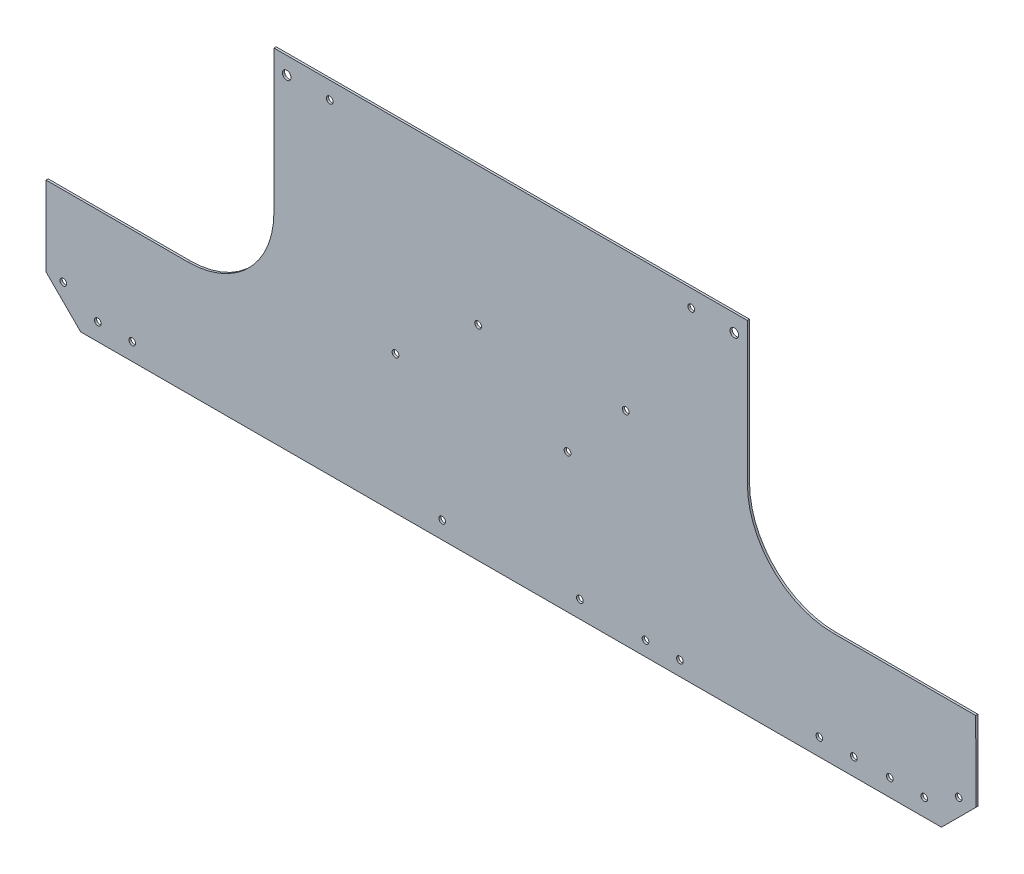
SolidWorks part; units mm, degrees
material "Perspex (TM) GS Acrylic Cast Sheet"
ref_plane "Front Plane" through (0, 0, 0) normal (0, 0, 1) x (1, 0, 0)
ref_plane "Top Plane" through (0, 0, 0) normal (0, 1, 0) x (1, 0, 0)
ref_plane "Right Plane" through (0, 0, 0) normal (1, 0, 0) x (0, 0, -1)
sketch "Sketch1" plane through (0, 0, 0) normal (0, 0, 1) x (1, 0, 0)
  line L1 (-457.2, -304.8) -> (457.2, -304.8)
  line L2 (-457.2, -304.8) -> (-457.2, 304.8)
  line L3 (-457.2, 304.8) -> (457.2, 304.8)
  line L4 (457.2, -304.8) -> (457.2, 304.8)
  line L5 (0, 304.8) -> (0, -304.8) construction
  line L6 (-457.2, 0) -> (457.2, 0) construction
  point P0 (0, 0)
  point P4 (-320.04, 0)
  point P5 (320.04, 0)
  point P6 (0, 213.36)
  point P7 (0, -213.36)
  dimension "Length" = 914.4
  dimension "Width" = 609.6
  dimension "Break" = 137.16
  dimension "D2" = 137.16
  dimension "D1" = 91.44
  dimension "D3" = 91.44
sketch "Sketch2" plane through (0, 0, 0) normal (1, 0, 0) x (0, 0, -1)
  line L0 (-0.7938, -304.8) -> (0.7938, -304.8)
  dimension "Thickness" = 1.5875
sketch "Sketch3" plane through (0, 0, 0) normal (0, 0, 1) x (1, 0, 0)
  line L0 (-457.2, -304.8) -> (-457.2, 304.8) construction
  line L1 (-457.2, -304.8) -> (457.2, -304.8) construction
  line L2 (457.2, -304.8) -> (457.2, 304.8) construction
  line L3 (-457.2, 304.8) -> (457.2, 304.8) construction
  line L4 (-457.2, -304.8) -> (-457.2, 304.8)
  line L5 (-457.2, -304.8) -> (457.2, -304.8)
  line L6 (457.2, -304.8) -> (457.2, 304.8)
  line L7 (-457.2, 304.8) -> (457.2, 304.8)
extrude "Boss-Extrude1" add sketch "Sketch3" along normal mid plane 1.5875
sketch "Sketch4" plane through (0, 0, 0.7937) normal (0, 0, 1) x (1, 0, 0)
  line L1 (-362.5066, 0.4474) -> (318.2125, 1.5649)
  line L2 (-339.2322, -251.9272) -> (-364.674, -226.4854)
  line L5 (-363.9625, -659.9558) -> (-365.0466, 0.4433) construction
  line L12 (-364.674, -226.4854) -> (-365.0424, -2.0967)
  line L15 (-339.2322, -251.9272) -> (295.7669, -250.8848)
  line L26 (295.7669, -250.8848) -> (321.1253, -225.5264)
  line L27 (320.7942, -23.8309) -> (321.8783, -684.23) construction
  line L28 (321.1253, -225.5264) -> (320.7567, -0.9709)
  arc A2 (318.2125, 1.5649) -> (320.7567, -0.9709) centre (318.2167, -0.9751) cw
  arc A3 (-362.5066, 0.4474) -> (-365.0424, -2.0967) centre (-362.5024, -2.0926) ccw
  point P12 (320.7525, 1.5691)
  point P15 (-365.0466, 0.4433)
  dimension "D1" = 2.54
  dimension "D2" = 2.54
extrude "Cut-Extrude1" cut sketch "Sketch4" against normal blind 2.54 flip side to cut
sketch "Sketch12" plane through (0, 0, -0.7937) normal (0, 0, -1) x (-1, 0, 0)
  line L1 (196.6362, -104.0919) -> (196.6362, 20.4048)
  line L19 (196.6362, 20.4048) -> (384.7638, 20.0959)
  line L20 (384.4556, -167.696) -> (384.7638, 20.0959)
  line L21 (260.0319, -167.696) -> (384.4556, -167.696)
  arc A2 (260.0319, -167.696) -> (196.6362, -104.0919) centre (260.1362, -104.1961) cw
sketch "Sketch9" plane through (0, 0, 0.7937) normal (0, 0, 1) x (1, 0, 0)
  point P0 (-365.5467, -279.4147)
  point P1 (-339.7911, -292.1147)
  point P3 (-314.3911, -292.1147)
  point P5 (-365.5467, -229.8463)
  point P15 (270.1645, -292.1147)
  point P17 (295.5645, -292.1147)
  point P19 (321.3201, -279.4147)
  point P21 (320.9651, -229.8463)
  point P23 (-219.4967, -52.0463)
  point P25 (174.9151, -52.0463)
hole_wizard "#10 (0.1935) Diameter Hole1" positions "Sketch10" profile "Sketch11" hole size "#10" standard "ANSI Inch" end condition through all
sketch "Sketch10" plane through (0, 0, 0.7937) normal (0, 0, 1) x (1, 0, 0)
  point P55 (-301.1531, -239.1647)
  point P58 (-326.5531, -239.2064)
  point P61 (-351.9739, -226.5481)
  point P64 (-72.5534, -238.7894)
  point P67 (29.0464, -238.6226)
  point P70 (77.4365, -240.4866)
  point P73 (102.8365, -240.4449)
  point P76 (205.7032, -238.3326)
  point P79 (231.1032, -238.2909)
  point P82 (257.6461, -238.2474)
  point P85 (283.0461, -238.2057)
  point P88 (308.4252, -225.464)
  point P91 (-155.476, -11.9127)
  point P94 (111.2237, -11.4749)
sketch "Sketch11" plane through (-301.1531, -239.1647, 0.7937) normal (1, 0, 0) x (0, -1, 0)
  line L0 (0, 0) -> (0, 1.5875)
  line L1 (0, 1.5875) -> (2.4574, 1.5875)
  line L2 (2.4574, 1.5875) -> (2.4574, 0)
  line L5 (2.4574, 0) -> (0, 0)
  line L11 (0, -6.35) -> (0, 107.95) construction
  dimension "Thru Hole Dia." = 4.9149
  dimension "Thru Hole Depth" = 1.5875
sketch "Sketch13" plane through (0, 0, -0.7937) normal (0, 0, -1) x (-1, 0, 0)
  line L1 (-216.2174, -166.8413) -> (-343.254, -166.8413)
  line L4 (-152.6132, -103.2371) -> (-152.6132, 23.5181)
  line L11 (-152.6132, 23.5181) -> (-342.941, 23.8305)
  line L12 (-343.254, -166.8413) -> (-342.941, 23.8305)
  arc A0 (-152.6132, -103.2371) -> (-216.2174, -166.8413) centre (-216.1131, -103.3413) cw
extrude "Cut-Extrude5" cut sketch "Sketch13" against normal blind 2.54
extrude "Cut-Extrude6" cut sketch "Sketch12" against normal blind 2.54
hole_wizard "1/4 (0.25) Diameter Hole1" positions "Sketch14" profile "Sketch15" hole size "1/4" standard "ANSI Inch" end condition through all
sketch "Sketch14" plane through (0, 0, -0.7937) normal (0, 0, -1) x (-1, 0, 0)
  point P0 (-142.9736, -11.4228)
  point P3 (187.2259, -11.9648)
sketch "Sketch15" plane through (142.9736, -11.4228, -0.7937) normal (1, 0, 0) x (0, 1, 0)
  line L0 (0, 0) -> (0, 1.5875)
  line L1 (0, 1.5875) -> (3.175, 1.5875)
  line L2 (3.175, 1.5875) -> (3.175, 0)
  line L5 (3.175, 0) -> (0, 0)
  line L11 (0, -6.35) -> (0, 107.95) construction
  dimension "Thru Hole Dia." = 6.35
  dimension "Thru Hole Depth" = 1.5875
hole_wizard "#10 Clearance Hole1" positions "Sketch16" profile "Sketch17" hole size "#10" standard "ANSI Inch" end condition through all
sketch "Sketch16" plane through (0, 0, -0.7937) normal (0, 0, -1) x (-1, 0, 0)
  point P0 (-62.8852, -101.187)
  point P2 (-19.9172, -149.0072)
  point P4 (46.0272, -100.8173)
  point P6 (106.9738, -149.7616)
sketch "Sketch17" plane through (62.8852, -101.187, -0.7937) normal (1, 0, 0) x (0, 1, 0)
  line L0 (0, 0) -> (0, 1.5875)
  line L1 (0, 1.5875) -> (2.4892, 1.5875)
  line L2 (2.4892, 1.5875) -> (2.4892, 0)
  line L5 (2.4892, 0) -> (0, 0)
  line L11 (0, -6.35) -> (0, 107.95) construction
  dimension "Thru Hole Dia." = 4.9784
  dimension "Thru Hole Depth" = 1.5875
equation "\"D1@Boss-Extrude1\"=\"thickness@sketch2\""
equation "\"Break@Sketch1\" = \"Length@Sketch1\" * 0.15"
equation "\"D2@Sketch1\" = \"Break@Sketch1\""
equation "\"D1@Sketch1\"=\"Width@Sketch1\"*0.15"
equation "\"D3@Sketch1\"=\"D1@Sketch1\""
